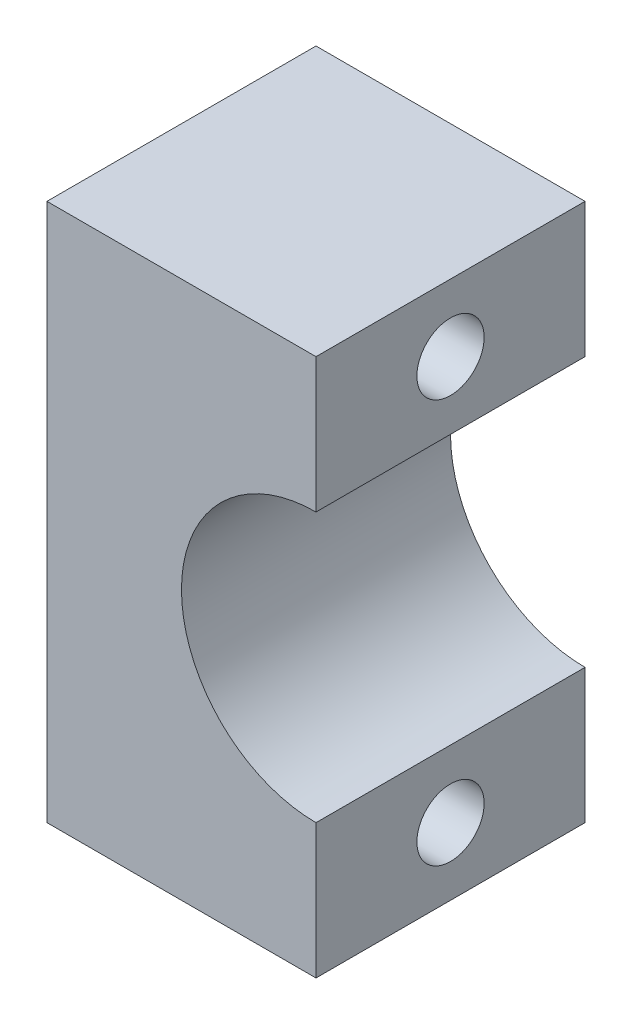
SolidWorks part; units mm, degrees
ref_plane "前视基准面" through (0, 0, 0) normal (0, 0, 1) x (1, 0, 0)
ref_plane "上视基准面" through (0, 0, 0) normal (0, 1, 0) x (1, 0, 0)
ref_plane "右视基准面" through (0, 0, 0) normal (1, 0, 0) x (0, 0, -1)
sketch "草图1" plane through (0, 0, 0) normal (0, 0, 1) x (1, 0, 0)
  line L5 (0, 20) -> (0, 10)
  line L6 (-20, 20) -> (0, 20)
  line L10 (-20, 20) -> (-20, -20)
  line L11 (-20, -20) -> (0, -20)
  line L13 (-20, 20) -> (-7.0711, 7.0711) construction
  line L14 (-20, -20) -> (-7.0711, -7.0711) construction
  line L15 (0, -10) -> (0, -20)
  arc A1 (0, 10) -> (0, -10) centre (0, 0) ccw
extrude "凸台-拉伸1" add sketch "草图1" along normal blind 20
sketch "草图3" plane through (0, 0, 0) normal (1, 0, 0) x (0, 0, -1)
  line L0 (-10, 20) -> (-10, -20) construction
  line L1 (-20, 20) -> (0, 20) construction
  line L2 (-20, -20) -> (0, -20) construction
  line L3 (-20, 15) -> (0, 15) construction
  line L4 (-20, 10) -> (-20, 20) construction
  line L5 (0, 10) -> (0, 20) construction
  line L6 (-20, -15) -> (0, -15) construction
  line L7 (-20, -20) -> (-20, -10) construction
  line L8 (0, -20) -> (0, -10) construction
  circle A0 centre (-10, 15) radius 2.5
  circle A1 centre (-10, -15) radius 2.5
extrude "切除-拉伸1" cut sketch "草图3" against normal blind 20
ref_plane "基准面4" through (-20, 0, 0) normal (1, 0, 0) x (0, 0, -1)
sketch "草图9" plane through (-20, 0, 0) normal (1, 0, 0) x (0, 0, -1)
  line L0 (-10, -20) -> (-10, 20) construction
  line L1 (-20, -20) -> (0, -20) construction
  line L2 (-20, 20) -> (0, 20) construction
  line L3 (0, 0) -> (-20, 0) construction
  line L4 (-20, 20) -> (-20, -20) construction
  line L6 (-6.7395, 6.0105) -> (-13.2605, 6.0105)
  line L7 (-6.7395, 6.0105) -> (-6.7395, -6.0105)
  line L8 (-6.7395, -6.0105) -> (-13.2605, -6.0105)
  line L9 (-13.2605, 6.0105) -> (-13.2605, -6.0105)
  line L10 (-6.7395, 6.0105) -> (-13.2605, -6.0105) construction
  line L11 (-6.7395, -6.0105) -> (-13.2605, 6.0105) construction
  point P11 (-10, 0)
extrude "切除-拉伸4" cut sketch "草图9" along normal blind 5
sketch "草图10" plane through (0, 0, 0) normal (0, 0, 1) x (1, 0, 0)
  line L0 (0, 0) -> (-20, 0) construction
  line L1 (-20, -11) -> (-20, 11) construction
  circle A1 centre (-16.5776, 0) radius 1
extrude "切除-拉伸6" cut sketch "草图10" along normal blind 7
